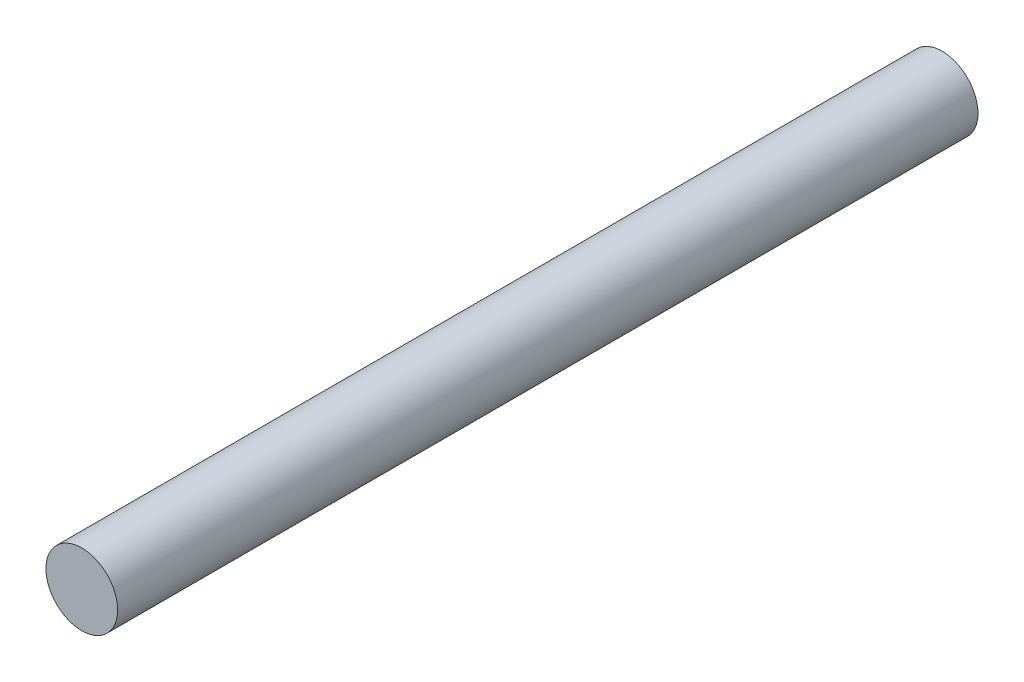
SolidWorks part; units mm, degrees
ref_plane "Front Plane" through (0, 0, 0) normal (0, 0, 1) x (1, 0, 0)
ref_plane "Top Plane" through (0, 0, 0) normal (0, 1, 0) x (1, 0, 0)
ref_plane "Right Plane" through (0, 0, 0) normal (1, 0, 0) x (0, 0, -1)
sketch "Sketch1" plane through (0, 0, 0) normal (0, 0, 1) x (1, 0, 0)
  circle A0 centre (0, 0) radius 3
  dimension "D1" = 6
extrude "Boss-Extrude1" add sketch "Sketch1" along normal blind 72
